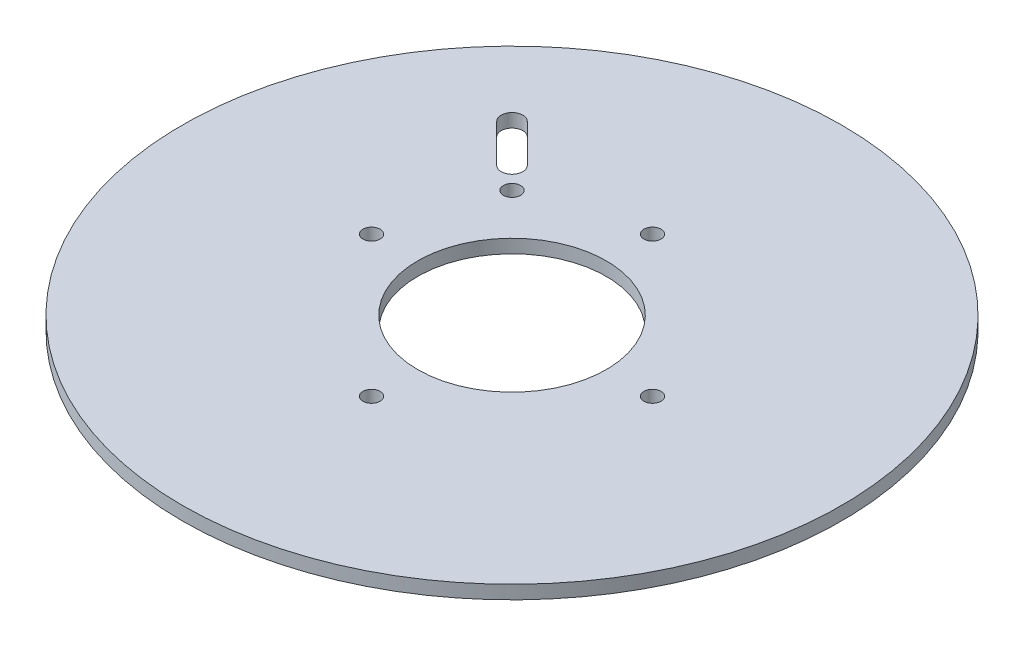
SolidWorks part; units mm, degrees
material "Acrylic (Medium-high impact)"
ref_plane "Front" through (0, 0, 0) normal (0, 0, 1) x (1, 0, 0)
ref_plane "Top" through (0, 0, 0) normal (0, 1, 0) x (1, 0, 0)
ref_plane "Right" through (0, 0, 0) normal (1, 0, 0) x (0, 0, -1)
sketch "Sketch1" plane through (0, 0, 0) normal (0, 1, 0) x (1, 0, 0)
  circle A0 centre (0, 0) radius 77.46
  dimension "D1" = 154.92
extrude "Boss-Extrude1" add sketch "Sketch1" along normal blind 3.175
sketch "Sketch24" plane through (0, 3.175, 0) normal (0, 1, 0) x (1, 0, 0)
  line L0 (-30.48, 30.48) -> (-39.4603, 39.4603) construction
  line L1 (-32.2761, 28.6839) -> (-41.2563, 37.6642)
  line L2 (-28.6839, 32.2761) -> (-37.6642, 41.2563)
  line L3 (0, 0) -> (54.9317, 0) construction
  circle A0 centre (0, 0) radius 22.1615
  circle A1 centre (0, 0) radius 33.02 construction
  circle A2 centre (-25.4, 25.4) radius 2.0193
  circle A3 centre (0, 33.02) radius 2.0193
  circle A4 centre (33.02, 0) radius 2.0193
  circle A5 centre (0, -33.02) radius 2.0193
  circle A6 centre (-33.02, 0) radius 2.0193
  arc A7 (-32.2761, 28.6839) -> (-28.6839, 32.2761) centre (-30.48, 30.48) ccw
  arc A8 (-37.6642, 41.2563) -> (-41.2563, 37.6642) centre (-39.4603, 39.4603) ccw
  point P16 (-34.9701, 34.9701)
  dimension "D1" = 4.0386
  dimension "D2" = 44.323
  dimension "D9" = 2.54
  dimension "D3" = 33.02
  dimension "D4" = 25.4
  dimension "D5" = 25.4
  dimension "D6" = 30.48
  dimension "D7" = 30.48
  dimension "D8" = 12.7
  dimension "D10" = 45
extrude "Cut-Extrude14" cut sketch "Sketch24" against normal through all
